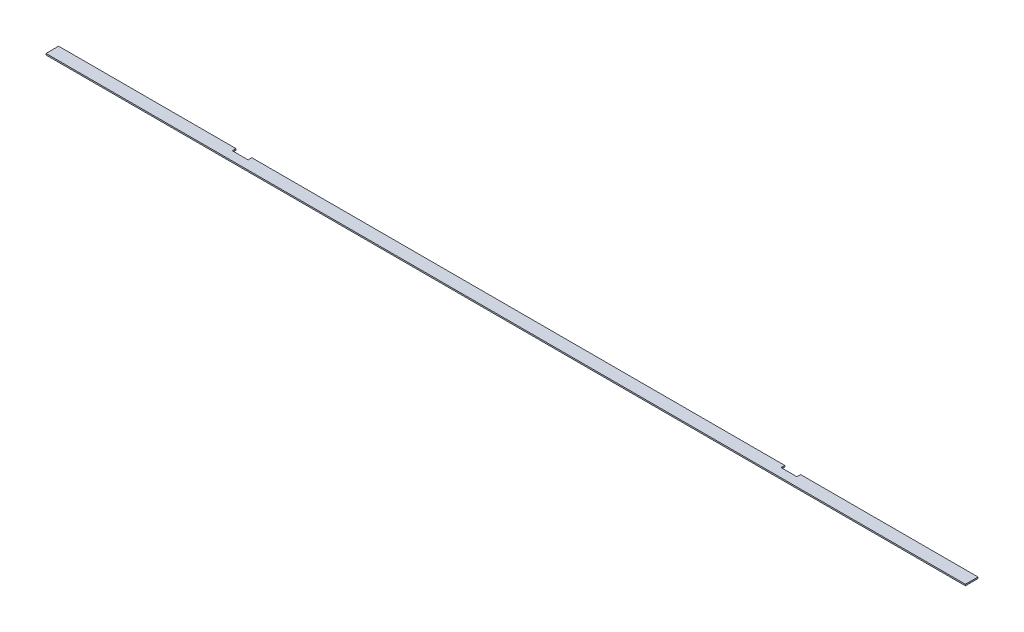
SolidWorks part; units mm, degrees
material "12Х18Н10Т ГОСТ 4543-71"
ref_plane "Спереди" through (0, 0, 0) normal (0, 0, 1) x (1, 0, 0)
ref_plane "Сверху" through (0, 0, 0) normal (0, 1, 0) x (1, 0, 0)
ref_plane "Справа" through (0, 0, 0) normal (1, 0, 0) x (0, 0, -1)
sketch "Эскиз1" plane through (0, 0, 0) normal (1, 0, 0) x (0, 0, -1)
  line L1 (-13.5, -1.5) -> (13.5, -1.5)
  line L2 (-13.5, -1.5) -> (-13.5, 1.5)
  line L3 (-13.5, 1.5) -> (13.5, 1.5)
  line L4 (13.5, -1.5) -> (13.5, 1.5)
  line L5 (0, 1.5) -> (0, -1.5) construction
  line L6 (-13.5, 0) -> (13.5, 0) construction
  point P0 (0, 0)
  dimension "D1" = 27
  dimension "D2" = 3
extrude "Бобышка-Вытянуть1" add sketch "Эскиз1" along normal mid plane 1970
sketch "Эскиз2" plane through (0, -1.5, 0) normal (0, -1, 0) x (1, 0, 0)
  line L0 (-573, -38.2904) -> (-573, -43.6277) construction
  line L1 (-573, -7.5) -> (-573, -26.053) construction
  line L2 (-603, -38.2904) -> (-603, -43.6277) construction
  line L3 (-603, -7.5) -> (-603, -26.053) construction
  line L4 (-603, -7.5) -> (-573, -7.5) construction
  line L5 (-603, -26.053) -> (-573, -26.053) construction
  line L6 (985, -13.5) -> (-985, -13.5) construction
  line L7 (-605, -28.053) -> (-571, -28.053)
  line L8 (-571, -5.5) -> (-571, -28.053)
  line L9 (-605, -5.5) -> (-571, -5.5)
  line L10 (-605, -5.5) -> (-605, -28.053)
  dimension "D1" = 6
  dimension "D2" = 2
extrude "Вырез-Вытянуть1" cut sketch "Эскиз2" against normal up to next
mirror "Зеркальное отражение1" about plane through (0, 0, 0) normal (1, 0, 0) of "Вырез-Вытянуть1"
